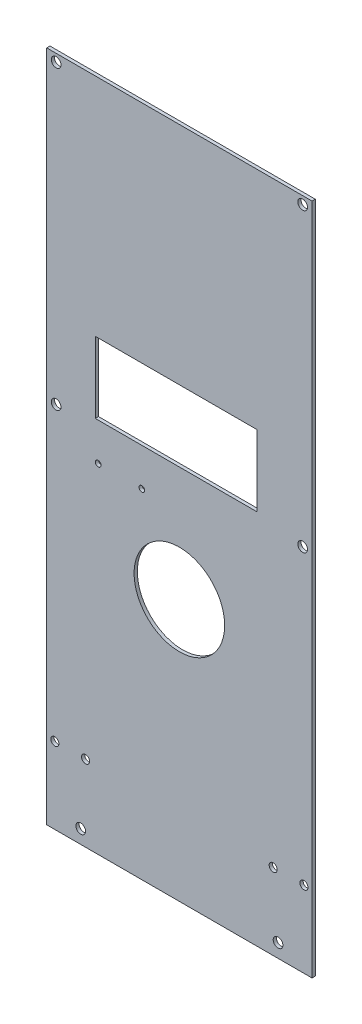
SolidWorks part; units mm, degrees
material "CFRP"
ref_plane "Front Plane" through (0, 0, 0) normal (0, 0, 1) x (1, 0, 0)
ref_plane "Top Plane" through (0, 0, 0) normal (0, 1, 0) x (1, 0, 0)
ref_plane "Right Plane" through (0, 0, 0) normal (1, 0, 0) x (0, 0, -1)
sketch "Sketch1" plane through (0, 0, 0) normal (0, 0, 1) x (1, 0, 0)
  line L1 (41, -104) -> (-41, -104)
  line L2 (41, -104) -> (41, 104)
  line L3 (41, 104) -> (-41, 104)
  line L4 (-41, -104) -> (-41, 104)
  line L5 (41, -104) -> (-41, 104) construction
  line L6 (41, 104) -> (-41, -104) construction
  point P0 (0, 0)
  dimension "D1" = 82
  dimension "D2" = 208
extrude "Boss-Extrude1" add sketch "Sketch1" along normal blind 1
hole_wizard "Ø3.0 (3) Diameter Hole1" positions "Sketch3" profile "Sketch2" hole size "Ø3.0" standard "ANSI Metric"
sketch "Sketch3" plane through (0, 0, 1) normal (0, 0, 1) x (1, 0, 0)
  line L7 (41, 104) -> (-41, 104) construction
  line L8 (0, 104) -> (0, -29.3752) construction
  point P0 (-38.1, 10)
  point P2 (38.1, 10)
  point P15 (30.5, -99.75)
  point P17 (-30.5, -99.75)
  point P36 (-38.1, 101.6)
  point P40 (38.1, 101.6)
  dimension "D3" = 94
  dimension "D5" = 94
  dimension "D7" = 38.1
  dimension "D8" = 38.1
  dimension "D9" = 38.1
  dimension "D10" = 38.1
sketch "Sketch2" plane through (-38.1, 10, 1) normal (1, 0, 0) x (0, -1, 0)
  line L0 (0, 0) -> (0, 1)
  line L1 (0, 1) -> (1.5, 1)
  line L2 (1.5, 1) -> (1.5, 0)
  line L5 (1.5, 0) -> (0, 0)
  line L10 (0, 1) -> (-1.5, 1) construction
  line L11 (0, -6.35) -> (0, 107.95) construction
  dimension "Hole Dia." = 3
  dimension "Hole Depth" = 1
  dimension "Drill Angle" = 180
sketch "Sketch8" plane through (0, 0, 1) normal (0, 0, 1) x (1, 0, 0)
  circle A0 centre (0, -23.15) radius 14
  dimension "D1" = 28
extrude "Cut-Extrude1" cut sketch "Sketch8" against normal blind 10
sketch "Sketch11" plane through (0, 0, 1) normal (0, 0, 1) x (1, 0, 0)
  line L1 (-26, 12.3) -> (24, 12.3)
  line L2 (-26, 12.3) -> (-26, 34.3)
  line L3 (-26, 34.3) -> (24, 34.3)
  line L4 (24, 12.3) -> (24, 34.3)
  line L6 (-41, 104) -> (-41, -104) construction
  line L7 (41, 104) -> (-41, 104) construction
  dimension "D1" = 50
  dimension "D2" = 22
  dimension "D3" = 15
  dimension "D4" = 69.7
extrude "Cut-Extrude2" cut sketch "Sketch11" against normal blind 10
hole_wizard "Ø2.5 (2.5) Diameter Hole1" positions "Sketch13" profile "Sketch12" hole size "Ø2.5" standard "ANSI Metric" end condition through all
sketch "Sketch13" plane through (0, 0, 1) normal (0, 0, 1) x (1, 0, 0)
  point P0 (-38.5, -80.4028)
  point P3 (-29, -80.4028)
  point P6 (29, -80.4028)
  point P9 (38.5, -80.4028)
sketch "Sketch12" plane through (-38.5, -80.4028, 1) normal (1, 0, 0) x (0, -1, 0)
  line L0 (0, 0) -> (0, 1)
  line L1 (0, 1) -> (1.25, 1)
  line L2 (1.25, 1) -> (1.25, 0)
  line L5 (1.25, 0) -> (0, 0)
  line L11 (0, -6.35) -> (0, 107.95) construction
  dimension "Thru Hole Dia." = 2.5
  dimension "Thru Hole Depth" = 1
hole_wizard "Ø1.75 (1.75) Diameter Hole1" positions "Sketch15" profile "Sketch14" hole size "Ø1.75" standard "ANSI Metric" end condition through all
sketch "Sketch15" plane through (0, 0, 1) normal (0, 0, 1) x (1, 0, 0)
  line L0 (-41, 104) -> (-41, -104) construction
  point P0 (-25.1, 0.65)
  point P2 (-11.6, 0.65)
  dimension "D1" = 15.9
sketch "Sketch14" plane through (-25.1, 0.65, 1) normal (1, 0, 0) x (0, -1, 0)
  line L0 (0, 0) -> (0, 1)
  line L1 (0, 1) -> (0.875, 1)
  line L2 (0.875, 1) -> (0.875, 0)
  line L5 (0.875, 0) -> (0, 0)
  line L11 (0, -6.35) -> (0, 107.95) construction
  dimension "Thru Hole Dia." = 1.75
  dimension "Thru Hole Depth" = 1
